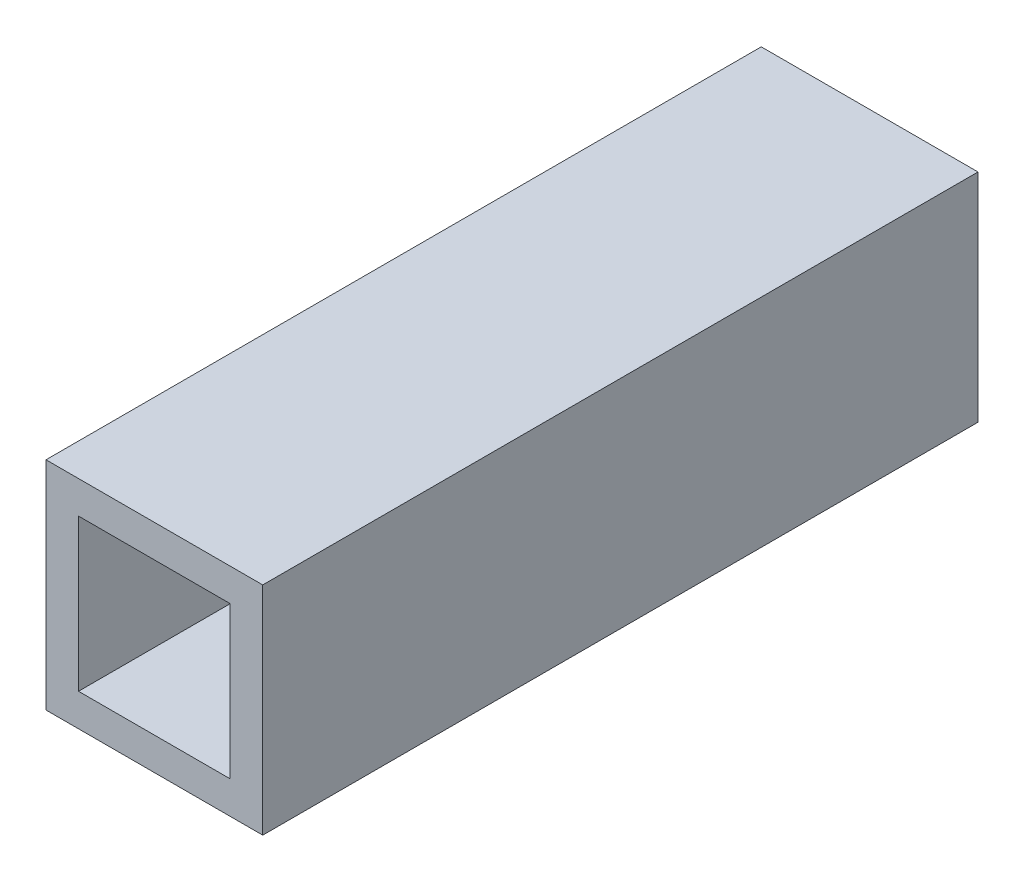
SolidWorks part; units mm, degrees
ref_plane "Front Plane" through (0, 0, 0) normal (0, 0, 1) x (1, 0, 0)
ref_plane "Top Plane" through (0, 0, 0) normal (0, 1, 0) x (1, 0, 0)
ref_plane "Right Plane" through (0, 0, 0) normal (1, 0, 0) x (0, 0, -1)
sketch "Sketch1" plane through (0, 0, 0) normal (0, 0, 1) x (1, 0, 0)
  line L1 (0, 0) -> (20, 0)
  line L2 (0, 0) -> (0, 20)
  line L3 (0, 20) -> (20, 20)
  line L4 (20, 0) -> (20, 20)
  dimension "D1" = 20
  dimension "D2" = 20
extrude "Boss-Extrude1" add sketch "Sketch1" along normal blind 66
shell "Shell1" thickness 3
